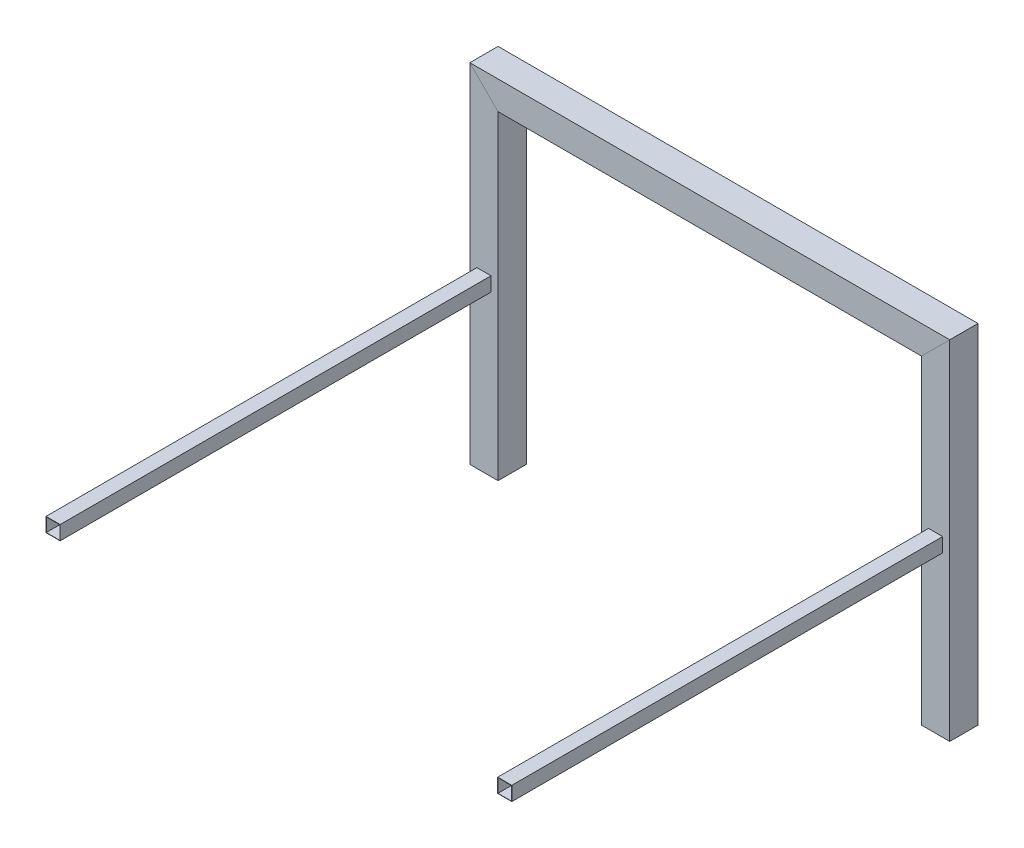
SolidWorks part; units mm, degrees
ref_plane "Alzado" through (0, 0, 0) normal (0, 0, 1) x (1, 0, 0)
ref_plane "Planta" through (0, 0, 0) normal (0, 1, 0) x (1, 0, 0)
ref_plane "Vista lateral" through (0, 0, 0) normal (1, 0, 0) x (0, 0, -1)
sketch3d "Croquis3D1"
  line L0 (0, 0, 0) -> (0, 600, 0)
  line L1 (0, 600, 0) -> (812, 600, 0)
  line L2 (812, 600, 0) -> (812, 0, 0)
  line L3 (0, 300, 0) -> (0, 300, 800)
  line L4 (812, 300, 0) -> (812, 300, 800)
  line L5 (78.5, 300, 800) -> (78.5, 300, 900)
  line L6 (733.5, 300, 800) -> (733.5, 300, 900)
  line L7 (0, 300, 800) -> (812, 300, 800)
  dimension "D1" = 600
  dimension "D2" = 812
  dimension "D3" = 800
  dimension "D4" = 78.5
  dimension "D6" = 78.5
  dimension "D5" = 100
other "Al tube (square) 2 SQ X .049 WALL(3)"
ref_plane "Plano1" through (0, 0, 0) normal (0, 1, 0) x (1, 0, 0)
sketch "Sketch11" plane through (0, 0, 0) normal (0, 1, 0) x (1, 0, 0)
  line L0 (-24.1554, -24.1554) -> (-24.1554, 24.1554)
  line L1 (24.1554, 24.1554) -> (-24.1554, 24.1554)
  line L2 (24.1554, 24.1554) -> (24.1554, -24.1554)
  line L3 (-24.1554, -24.1554) -> (24.1554, -24.1554)
  line L4 (-25.4, -25.4) -> (25.4, -25.4)
  line L5 (-25.4, -25.4) -> (-25.4, 25.4)
  line L6 (25.4, 25.4) -> (-25.4, 25.4)
  line L7 (25.4, 25.4) -> (25.4, -25.4)
  line L8 (0, -24.1554) -> (0, -25.4) construction
  line L9 (0, -24.1554) -> (0, 24.1554) construction
  line L10 (0, 24.1554) -> (0, 25.4) construction
  line L11 (25.4, 0) -> (24.1554, 0) construction
  line L12 (24.1554, 0) -> (-24.1554, 0) construction
  line L13 (-24.1554, 0) -> (-25.4, 0) construction
  point P14 (0, 0)
  dimension "Thickness" = 1.2446
  dimension "V_leg" = 50.8
  dimension "H_leg" = 50.8
other "Al tube (square) 1 SQ X .022 WALL(7)"
ref_plane "Plano2" through (0, 300, 0) normal (0, 0, 1) x (1, 0, 0)
sketch "Sketch1" plane through (0, 300, 0) normal (0, 0, 1) x (1, 0, 0)
  line L0 (-12.1412, -12.1412) -> (-12.1412, 12.1412)
  line L1 (12.1412, 12.1412) -> (-12.1412, 12.1412)
  line L2 (12.1412, 12.1412) -> (12.1412, -12.1412)
  line L3 (-12.1412, -12.1412) -> (12.1412, -12.1412)
  line L4 (-12.7, -12.7) -> (12.7, -12.7)
  line L5 (-12.7, -12.7) -> (-12.7, 12.7)
  line L6 (12.7, 12.7) -> (-12.7, 12.7)
  line L7 (12.7, 12.7) -> (12.7, -12.7)
  line L8 (0, -12.1412) -> (0, -12.7) construction
  line L9 (0, -12.1412) -> (0, 12.1412) construction
  line L10 (0, 12.1412) -> (0, 12.7) construction
  line L11 (12.7, 0) -> (12.1412, 0) construction
  line L12 (12.1412, 0) -> (-12.1412, 0) construction
  line L13 (-12.1412, 0) -> (-12.7, 0) construction
  point P14 (0, 0)
  dimension "Thickness" = 0.5588
  dimension "V_leg" = 25.4
  dimension "H_leg" = 25.4
other "Recortar/Extender1"
